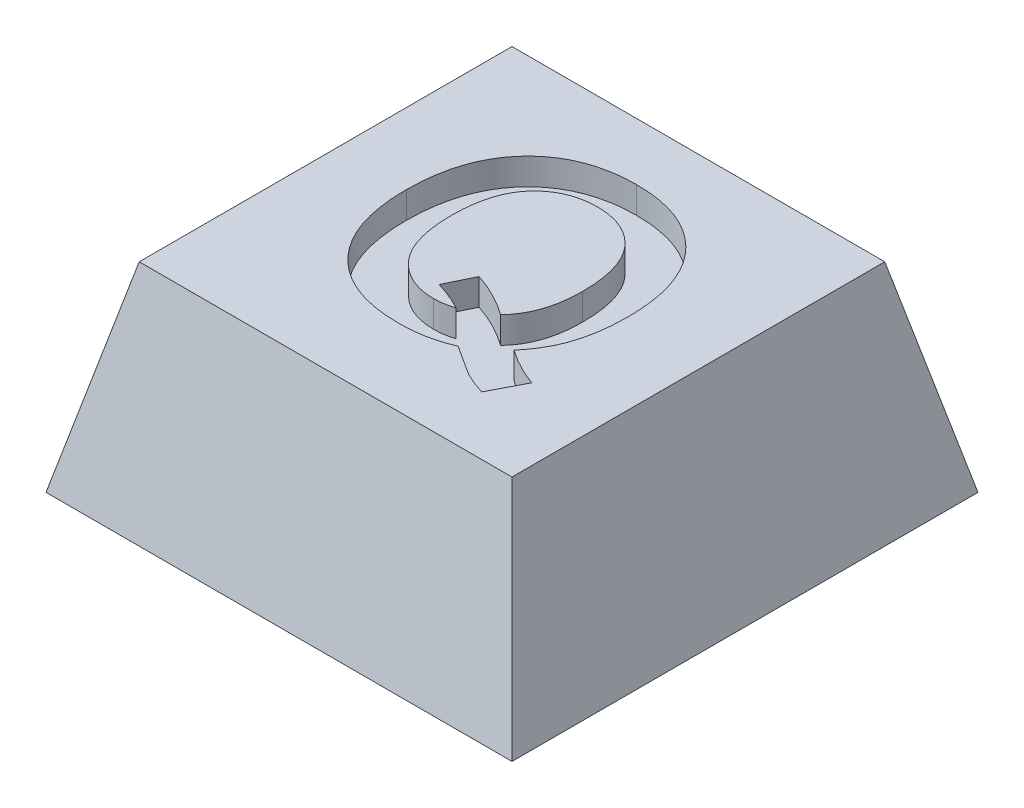
SolidWorks part; units mm, degrees
ref_plane "Front Plane" through (0, 0, 0) normal (0, 0, 1) x (1, 0, 0)
ref_plane "Top Plane" through (0, 0, 0) normal (0, 1, 0) x (1, 0, 0)
ref_plane "Right Plane" through (0, 0, 0) normal (1, 0, 0) x (0, 0, -1)
sketch "Sketch1" plane through (0, 0, 0) normal (0, 1, 0) x (1, 0, 0)
  line L1 (0, 0) -> (7, 0)
  line L2 (0, 0) -> (0, 7)
  line L3 (0, 7) -> (7, 7)
  line L4 (7, 0) -> (7, 7)
  dimension "D1" = 7
  dimension "D2" = 7
extrude "Boss-Extrude1" add sketch "Sketch1" along normal blind 3
sketch "Sketch2" plane through (0, 0, 0) normal (0, 0, 1) x (1, 0, 0)
  line L0 (0, 0) -> (0.7, 3)
  line L1 (0, 3) -> (7, 3) construction
  line L2 (0.7, 3) -> (0, 3)
  line L3 (0, 3) -> (0, 0)
  line L4 (7, 0) -> (6.3, 3)
  line L5 (6.3, 3) -> (7, 3)
  line L6 (7, 3) -> (7, 0)
  dimension "D1" = 0.7
  dimension "D2" = 0.7
extrude "Cut-Extrude1" cut sketch "Sketch2" against normal blind 7
sketch "Sketch3" plane through (0, 0, 0) normal (1, 0, 0) x (0, 0, -1)
  line L0 (0, 0) -> (0.7, 3)
  line L1 (7, 3) -> (0, 3) construction
  line L2 (0.7, 3) -> (0, 3)
  line L3 (0, 3) -> (0, 0)
  line L4 (7, 3) -> (6.3, 3)
  line L5 (6.3, 3) -> (7, 0)
  line L6 (7, 3) -> (7, 0)
  dimension "D1" = 0.7
  dimension "D2" = 0.7
extrude "Cut-Extrude2" cut sketch "Sketch3" along normal blind 11
sketch "Sketch4" plane through (0, 0, 0) normal (0, -1, 0) x (1, 0, 0)
  line L0 (3.5, 0) -> (3.5, -7) construction
  line L1 (0, 0) -> (7, 0) construction
  line L2 (7, -7) -> (0, -7) construction
  line L3 (0, -3.5) -> (7, -3.5) construction
  line L4 (0, -7) -> (0, 0) construction
  line L5 (7, 0) -> (7, -7) construction
  circle A0 centre (3.5, -3.5) radius 1.8
  dimension "D1" = 3.6
extrude "Cut-Extrude3" cut sketch "Sketch4" against normal blind 0.8
sketch "Sketch6" plane through (0, 3, 0) normal (0, 1, 0) x (1, 0, 0)
  text T0 "Q" font "Arial" height 3.5
extrude "Cut-Extrude4" cut sketch "Sketch6" against normal blind 0.4
